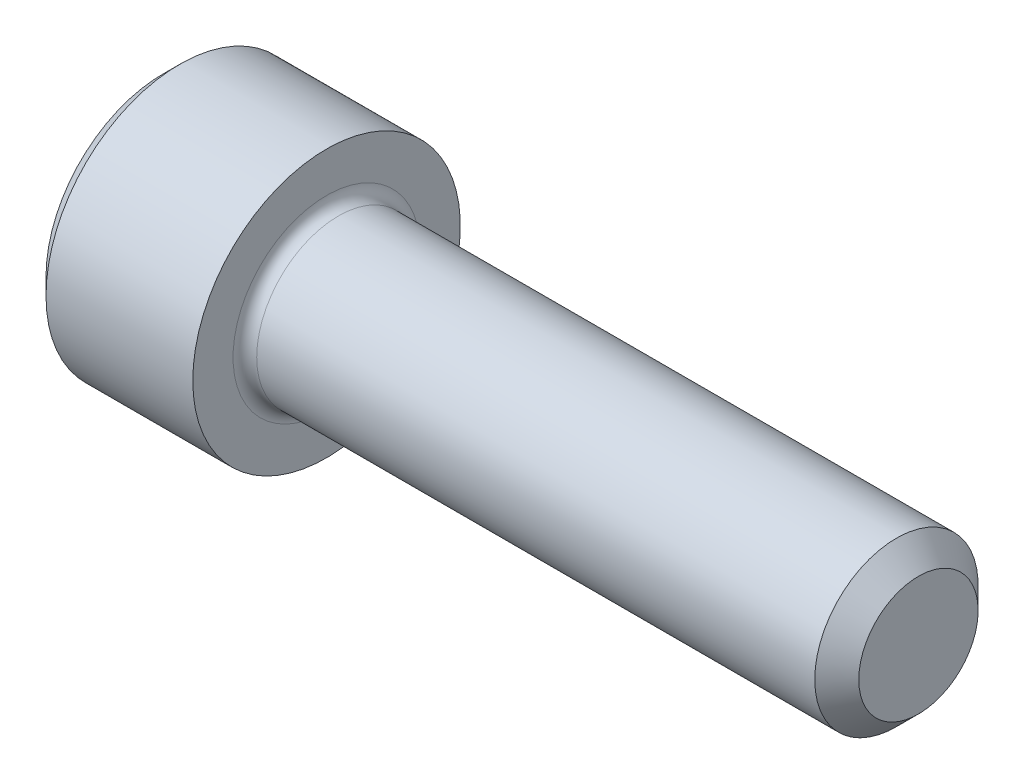
SolidWorks part; units mm, degrees
material "Alloy Steel"
ref_plane "Plane1" through (0, 0, 0) normal (0, 0, 1) x (1, 0, 0)
ref_plane "Plane2" through (0, 0, 0) normal (0, 1, 0) x (1, 0, 0)
ref_plane "Plane3" through (0, 0, 0) normal (1, 0, 0) x (0, 0, -1)
revolve "Base-Revolve" add sketch "BodySke"
sketch "BodySke" plane through (0, 0, 0) normal (0, 0, 1) x (1, 0, 0)
  line L0 (0, 0) -> (0, 2.5146)
  line L1 (0.3556, 2.8702) -> (3.5052, 2.8702)
  line L2 (3.5052, 2.8702) -> (3.5052, 1.7526)
  line L3 (3.5052, 1.7526) -> (15.7328, 1.7526)
  line L4 (16.2052, 1.2802) -> (16.2052, 0)
  line L5 (16.2052, 0) -> (0, 0)
  line L6 (-31.75, 0) -> (127, 0) construction
  line L7 (0, 2.5146) -> (0.3556, 2.8702)
  line L8 (16.2052, 1.2802) -> (15.7328, 1.7526)
  line L9 (0, -2.5146) -> (0.3556, -2.8702) construction
  line L10 (16.2052, -1.2802) -> (15.7328, -1.7526) construction
  line L11 (4.2977, 9.525) -> (4.2977, 3.175) construction
  line L12 (3.5052, 9.525) -> (3.5052, 3.175) construction
  line L13 (-21.8948, 9.525) -> (-21.8948, 3.175) construction
  dimension "Diameter" = 3.5052
  dimension "Head_ht" = 3.5052
  dimension "Length" = 12.7
  dimension "Body_ch_ang" = 45
  dimension "Head_dia" = 5.7404
  dimension "Head_ch_ang" = 45
  dimension "Head_side_ht" = 3.1496
  dimension "Minor_dia" = 2.5603
  dimension "Advance" = 0.7925
  dimension "Thread_nom" = 12.7
  dimension "Thread_length" = 38.1
cosmetic thread "ThreadCosmetic"
fillet "Fillet1" radius 0.254 1 edges at (3.5052, 0, 1.7526)
sketch "Sketch2" plane through (0, 0, 0) normal (0, 0, 1) x (1, 0, 0)
  line L0 (0, 1.3843) -> (1.6256, 1.3843)
  line L1 (1.6256, 1.3843) -> (2.4248, 0)
  line L2 (-31.75, 0) -> (127, 0) construction
  line L3 (2.4248, 0) -> (0, 0)
  line L4 (0, 0) -> (0, 1.3843)
  line L5 (0, 2.5146) -> (0, -2.5146) construction
  line L6 (0, 0) -> (47.625, 0) construction
  line L7 (3.5052, -2.8702) -> (3.5052, 2.8702) construction
  dimension "D1" = 1.3843
  dimension "D2" = 60
  dimension "Wall_thickness" = 1.8796
revolve "Hex-PreBroach" cut sketch "Sketch2" angle 360 about L6
sketch "Sketch3" plane through (0, 0, 0) normal (-1, 0, 0) x (0, 0.5, 0.866)
  line L0 (0.7992, 1.3843) -> (-0.7992, 1.3843)
  line L1 (-0.7992, 1.3843) -> (-1.5985, 0)
  line L2 (0.7992, 1.3843) -> (1.5985, 0)
  line L3 (0.7992, -1.3843) -> (1.5985, 0)
  line L4 (0.7992, -1.3843) -> (-0.7992, -1.3843)
  line L5 (-0.7992, -1.3843) -> (-1.5985, 0)
  dimension "D1" = 1.3843
  dimension "D2" = 1.3843
  dimension "Hex_size" = 2.7686
extrude "Hex" cut sketch "Sketch3" against normal blind 1.6256
sketch "Sketch4" plane through (0, 0, 0) normal (-1, 0, 0) x (0, 0, 1)
  line L0 (0, 0) -> (1.7399, 0)
  line L1 (0, 0) -> (6.1484, 3.5498) construction
  line L2 (0, 0) -> (0.8699, 1.5068)
  line L3 (1.4457, 0.3947) -> (1.6607, 0.5189)
  line L4 (1.0647, 1.0546) -> (1.2797, 1.1788)
  arc A0 (1.4457, 0.3947) -> (1.0647, 1.0546) centre (0, 0) ccw
  arc A1 (1.7399, 0) -> (1.6607, 0.5189) centre (0, 0) ccw
  arc A2 (0.8699, 1.5068) -> (1.2797, 1.1788) centre (0, 0) cw
  dimension "D1" = 30
  dimension "Spline_n_dim" = 2.9972
  dimension "Spline_m_dim" = 3.4798
  dimension "D2" = 60
  dimension "D3" = 0.381
  dimension "Spline_p_dim" = 0.762
extrude "Spline" [suppressed] cut sketch "Sketch4" against normal blind 1.6256
pattern_circular "CirPattern1" [suppressed] count 6 every 60
sketch "Sketch5" plane through (0, 0, 0) normal (0, 0, 1) x (1, 0, 0)
  line L0 (-31.75, 0) -> (127, 0) construction
  line L2 (0, 2.5146) -> (0, -2.5146) construction
  circle A0 centre (1.27, 0) radius 0.4445
  dimension "Drilled_hole_dia" = 0.889
  dimension "Drilled_hole_loc" = 1.27
extrude "Hole" [suppressed] cut sketch "Sketch5" against normal through all and the other way through all
pattern_circular "Drilled-4" [suppressed] count 2 every 60
pattern_circular "Drilled-6" [suppressed] count 3 every 60
sketch "ThdSchSke" plane through (0, 0, 0) normal (0, 0, 1) x (1, 0, 0)
  line L0 (4.2977, -1.2802) -> (3.9669, -1.7526)
  line L1 (4.2977, -1.2802) -> (4.6285, -1.7526)
  line L2 (4.6285, -1.7526) -> (4.6285, -2.1908)
  line L3 (-3.175, 0) -> (5.1513, 0) construction
  line L5 (4.6285, -2.1908) -> (3.9669, -2.1908)
  line L6 (3.9669, -2.1908) -> (3.9669, -1.7526)
  line L7 (0, 2.5146) -> (0, -2.5146) construction
  dimension "Thread_minor" = 2.5603
  dimension "Diameter" = 3.5052
  dimension "Start" = 4.2977
  dimension "SideAngle" = 55
  dimension "VeeAngle" = 70
  dimension "Overcut" = 4.3815
revolve "ThreadSchematic" [suppressed] cut sketch "ThdSchSke" angle 360 about L3
pattern_linear "ThdSchPat" [suppressed]
equation "\"D2@Sketch3\" = \"Hex_size@Sketch3\" / 2"
equation "\"D1@Sketch3\" = \"Hex_size@Sketch3\" / 2"
equation "\"D1@Sketch2\" = \"Hex_size@Sketch3\" / 2"
equation "\"D3@Sketch4\" = \"Spline_p_dim@Sketch4\" / 2"
equation "\"Thread_minor@ThreadCosmetic\"  =  \"Minor_dia@BodySke\""
equation "\"D2@CirPattern1\" = 360 / \"Num_teeth@CirPattern1\""
equation "\"Wall_thickness@Sketch2\" = \"Head_ht@BodySke\" - \"Key_eng@Hex\""
equation "\"Thread_length@ThreadCosmetic\" = ((sgn( (\"Length@BodySke\" - \"Advance@BodySke\" ) - \"Thread_nom@BodySke\" )-1)*( (\"Length@BodySke\" - \"Advance@BodySke\" ) - \"Thread_nom@BodySke\" ))/-2+ \"Thread_nom@BodySke\""
equation "\"Thread_minor@ThdSchSke\" = \"Minor_dia@BodySke\""
equation "\"Diameter@ThdSchSke\" = \"Diameter@BodySke\""
equation "\"Overcut@ThdSchSke\" = \"Diameter@BodySke\" * 1.25"
equation "\"Start@ThdSchSke\" = \"Head_ht@BodySke\" + \"Length@BodySke\" - \"Thread_length@ThreadCosmetic\"  '---Non-countersunk---"
equation "\"Num_threads@ThdSchPat\" = int( \"Thread_length@ThreadCosmetic\" / \"Advance@BodySke\" + 0.999 )  + 1"
equation "\"Advance@ThdSchPat\" = \"Thread_length@ThreadCosmetic\" /  (\"Num_threads@ThdSchPat\" - 1) 'relax it"
equation "\"Num_threads@ThdSchPat\" = \"Num_threads@ThdSchPat\" - sgn( \"Num_threads@ThdSchPat\" - 1) '---chamfered tips only---"
